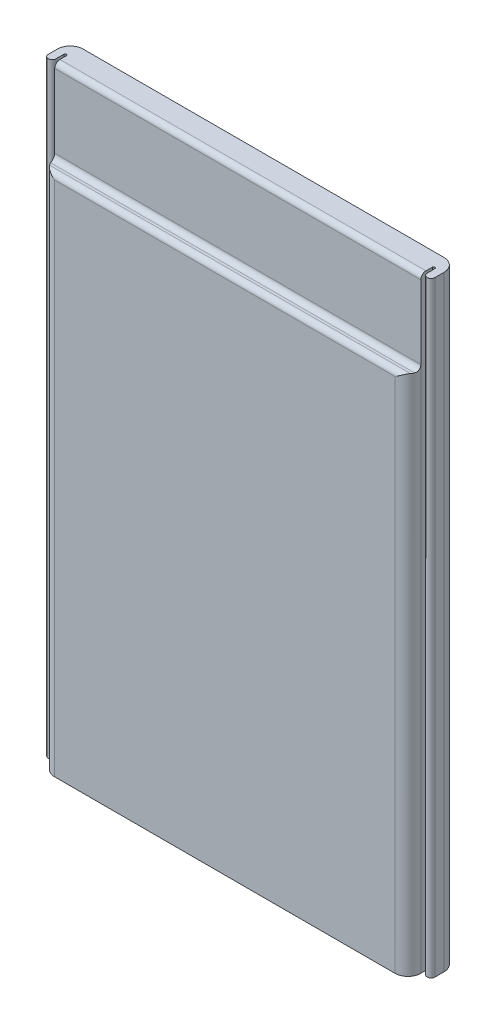
SolidWorks part; units mm, degrees
ref_plane "Front" through (0, 0, 0) normal (0, 0, 1) x (1, 0, 0)
ref_plane "Top" through (0, 0, 0) normal (0, 1, 0) x (1, 0, 0)
ref_plane "Right" through (0, 0, 0) normal (1, 0, 0) x (0, 0, -1)
sketch "Эскиз1" plane through (0, 0, 0) normal (0, 1, 0) x (1, 0, 0)
  line L0 (-14, 0) -> (14, 0)
  line L1 (-13.2, -3) -> (13.2, -3)
  line L2 (-15, -1) -> (-15, -1.7)
  line L3 (15, -1) -> (15, -1.7)
  line L4 (-14.2, -2) -> (-14.2, -1.1)
  line L5 (14.2, -1.1) -> (14.2, -2)
  line L6 (14.4, -1.7) -> (14.4, -1.1)
  line L7 (-14.4, -1.7) -> (-14.4, -1.1)
  arc A0 (-14, 0) -> (-15, -1) centre (-14, -1) ccw
  arc A1 (14, 0) -> (15, -1) centre (14, -1) cw
  arc A2 (-14.2, -2) -> (-13.2, -3) centre (-13.2, -2) ccw
  arc A3 (14.2, -2) -> (13.2, -3) centre (13.2, -2) cw
  arc A4 (15, -1.7) -> (14.4, -1.7) centre (14.7, -1.7) cw
  arc A5 (14.2, -1.1) -> (14.4, -1.1) centre (14.3, -1.1) cw
  arc A6 (-15, -1.7) -> (-14.4, -1.7) centre (-14.7, -1.7) ccw
  arc A7 (-14.2, -1.1) -> (-14.4, -1.1) centre (-14.3, -1.1) ccw
  point P20 (14.3, -1)
  point P21 (14.7, -2)
  point P27 (-14.3, -1)
  point P28 (-14.7, -2)
  dimension "D1" = 30
  dimension "D3" = 1
  dimension "D4" = 1
  dimension "D5" = 0.3
  dimension "D6" = 0.1
  dimension "D2" = 3
extrude "Бобышка-Вытянуть1" add sketch "Эскиз1" along normal mid plane 47
sketch "Эскиз2" plane through (0, 0, 0) normal (1, 0, 0) x (0, 0, -1)
  line L0 (-2, 23.1) -> (-2, 17.4)
  line L1 (-2.4, 17) -> (-2.6, 17)
  line L2 (-3, 23.5) -> (-3, 16.6)
  line L3 (-3, 23.5) -> (-3, -23.5) construction
  line L6 (-3, 23.5) -> (-1.6, 23.5)
  line L7 (0, 23.5) -> (-1, 23.5) construction
  arc A0 (-2, 17.4) -> (-2.4, 17) centre (-2.4, 17.4) cw
  arc A1 (-2.6, 17) -> (-3, 16.6) centre (-2.6, 16.6) ccw
  arc A2 (-1.6, 23.5) -> (-2, 23.1) centre (-1.6, 23.1) ccw
  dimension "D1" = 0.4
  dimension "D2" = 2
  dimension "D3" = 6.5
extrude "Вырез-Вытянуть1" cut sketch "Эскиз2" against normal up to next and the other way up to next
